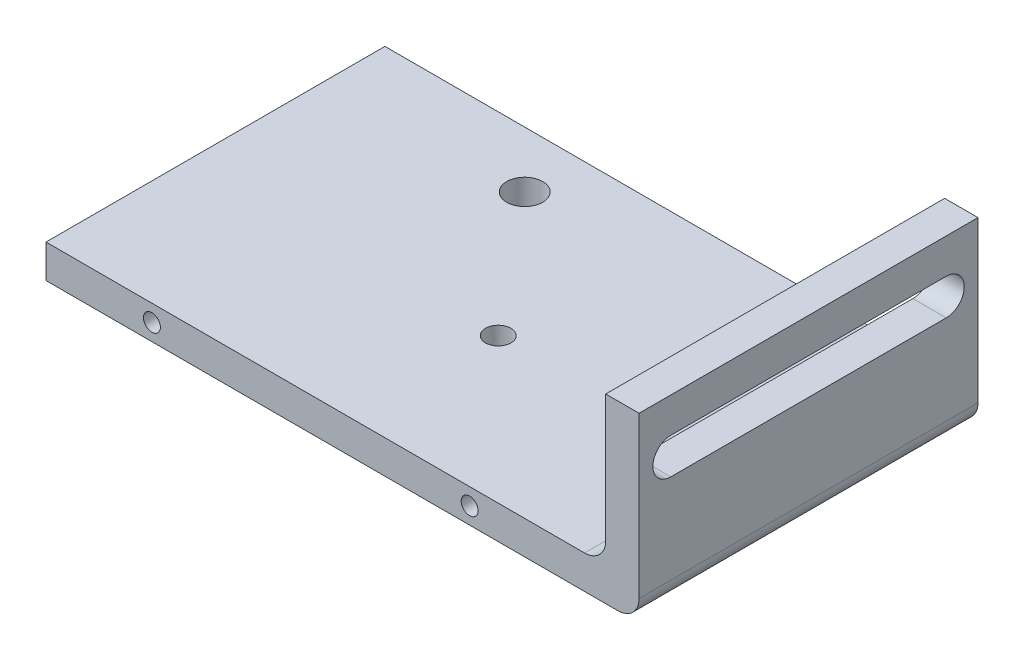
SolidWorks part; units mm, degrees
material "铜"
ref_plane "前视基准面" through (0, 0, 0) normal (0, 0, 1) x (1, 0, 0)
ref_plane "上视基准面" through (0, 0, 0) normal (0, 1, 0) x (1, 0, 0)
ref_plane "右视基准面" through (0, 0, 0) normal (1, 0, 0) x (0, 0, -1)
sketch "草图1" plane through (0, 0, 0) normal (0, 1, 0) x (1, 0, 0)
  line L1 (-35.5, 16) -> (35.5, 16)
  line L2 (-35.5, 16) -> (-35.5, -16)
  line L3 (-35.5, -16) -> (35.5, -16)
  line L4 (35.5, 16) -> (35.5, -16)
  line L5 (-35.5, 16) -> (35.5, -16) construction
  line L6 (-35.5, -16) -> (35.5, 16) construction
  point P0 (0, 0)
  dimension "D1" = 32
  dimension "D2" = 71
extrude "凸台-拉伸1" add sketch "草图1" along normal blind 3.15
sketch "草图2" plane through (0, 3.15, 0) normal (0, 1, 0) x (1, 0, 0)
  line L0 (35.5, -16) -> (35.5, 16)
  line L1 (35.5, -16) -> (32.35, -16)
  line L2 (35.5, 16) -> (32.35, 16)
  line L3 (32.35, -16) -> (32.35, 16)
  dimension "D1" = 3.15
extrude "凸台-拉伸2" add sketch "草图2" along normal blind 14
fillet "圆角1" radius 2 2 edges at (35.5, 0, 0)
sketch "草图3" plane through (0, 0, 0) normal (0, -1, 0) x (1, 0, 0)
  circle A2 centre (-2, -10.7) radius 1.7
  circle A3 centre (8.5, 2.3) radius 1.2
extrude "切除-拉伸1" cut sketch "草图3" against normal through all
sketch "草图4" plane through (0, 0, 16) normal (0, 0, 1) x (1, 0, 0)
  line L0 (-35.5, 3.15) -> (-35.5, 0) construction
  line L1 (-35.5, 0) -> (33.5, 0) construction
  point P0 (19.5, 1.575)
  point P1 (-35.5, 1.575)
  dimension "D1" = 55
  dimension "D2" = 1.575
hole_wizard "M2x0.4 螺纹孔1" positions "3D草图1" profile "草图5" tap size "M2x0.4" standard "ANSI Metric"
sketch3d "3D草图1"
  point P0 (19.5, 1.575, 16)
sketch "草图5" plane through (19.5, 1.575, 16) normal (1, 0, 0) x (0, -1, 0)
  line L0 (0, 0) -> (0, 5.6807)
  line L1 (0, 5.6807) -> (0.8, 5.2)
  line L2 (0.8, 5.2) -> (0.8, 0)
  line L5 (0.8, 0) -> (0, 0)
  line L10 (0, 5.6807) -> (-0.8, 5.2) construction
  line L11 (0, -6.35) -> (0, 107.95) construction
  dimension "螺纹孔钻头直径" = 1.6
  dimension "螺纹孔钻头深度" = 5.2
  dimension "导头角度" = 118
cosmetic thread "孔螺蚊线1" parameters "D1"=4, "D2"=2
mirror "镜向1" about plane through (0, 0, 0) normal (0, 0, 1) of "M2x0.4 螺纹孔1"
sketch "草图6" plane through (35.5, 0, 0) normal (1, 0, 0) x (0, 0, -1)
  line L0 (-13, 12.15) -> (13, 12.15) construction
  line L1 (-13, 13.85) -> (13, 13.85)
  line L2 (-13, 10.45) -> (13, 10.45)
  line L3 (-16, 17.15) -> (16, 17.15) construction
  line L4 (-16, 17.15) -> (-16, 2) construction
  arc A0 (-13, 13.85) -> (-13, 10.45) centre (-13, 12.15) ccw
  arc A1 (13, 10.45) -> (13, 13.85) centre (13, 12.15) ccw
  point P2 (0, 12.15)
  dimension "D3" = 26
  dimension "D4" = 3
  dimension "D1" = 3.4
  dimension "D2" = 5
extrude "切除-拉伸2" cut sketch "草图6" against normal through all
sketch "草图7" plane through (-35.5, 0, 0) normal (-1, 0, 0) x (0, 0, 1)
  line L1 (-16, 3.15) -> (16, 3.15)
  line L2 (-16, 3.15) -> (-16, 0)
  line L3 (-16, 0) -> (16, 0)
  line L4 (16, 3.15) -> (16, 0)
extrude "切除-拉伸3" cut sketch "草图7" against normal blind 15
sketch "草图12" plane through (0, 0, 16) normal (0, 0, 1) x (1, 0, 0)
  line L0 (-20.5, 3.15) -> (30.35, 3.15) construction
  circle A0 centre (-10.5, 1.575) radius 0.8
  dimension "D1" = 1.6
  dimension "D2" = 30
  dimension "D3" = 1.575
sketch "草图13" plane through (0, 0, -16) normal (0, 0, -1) x (-1, 0, 0)
  line L0 (-30.35, 3.15) -> (20.5, 3.15) construction
  circle A0 centre (10.5, 1.575) radius 0.8
  dimension "D1" = 1.6
  dimension "D2" = 30
  dimension "D3" = 1.575
hole_wizard "M2 螺纹孔2" positions "3D草图5" profile "草图14" tap size "M2" standard "GB"
sketch3d "3D草图5"
  point P0 (-10.5, 1.575, 16)
  point P3 (-10.5, 1.575, -16)
sketch "草图14" plane through (-10.5, 1.575, 16) normal (1, 0, 0) x (0, -1, 0)
  line L0 (0, 0) -> (0, 4.4807)
  line L1 (0, 4.4807) -> (0.8, 4)
  line L2 (0.8, 4) -> (0.8, 0)
  line L5 (0.8, 0) -> (0, 0)
  line L10 (0, 4.4807) -> (-0.8, 4) construction
  line L11 (0, -6.35) -> (0, 107.95) construction
  dimension "螺纹孔钻头直径" = 1.6
  dimension "螺纹孔钻头深度" = 4
  dimension "导头角度" = 118
cosmetic thread "孔螺蚊线3" parameters "D1"=4, "D2"=2
cosmetic thread "孔螺蚊线4" parameters "D1"=4, "D2"=2
